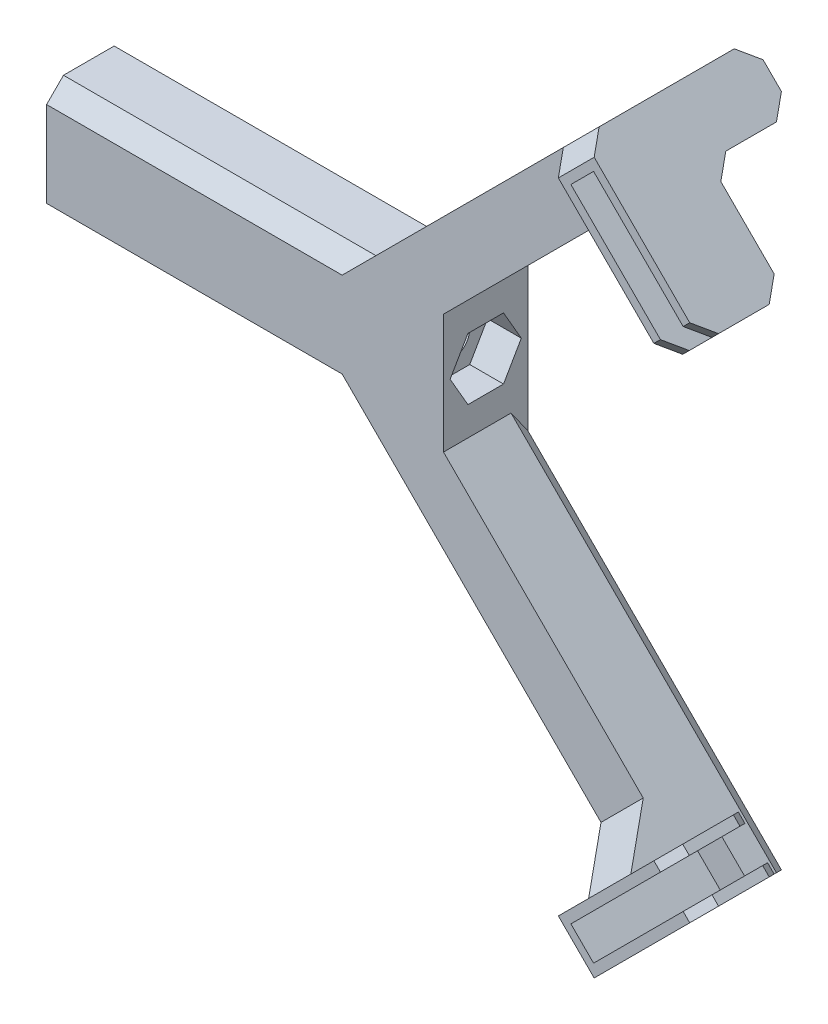
SolidWorks part; units mm, degrees
ref_plane "前视基准面" through (0, 0, 0) normal (0, 0, 1) x (1, 0, 0)
ref_plane "上视基准面" through (0, 0, 0) normal (0, 1, 0) x (1, 0, 0)
ref_plane "右视基准面" through (0, 0, 0) normal (1, 0, 0) x (0, 0, -1)
other "Configuration Table"
sketch "草图1" plane through (0, 0, 0) normal (0, 0, 1) x (1, 0, 0)
  line L0 (-10, 0) -> (33.5, 43.5)
  line L1 (33.5, 43.5) -> (38.5, 38.5)
  line L2 (38.5, 38.5) -> (0, 0)
  line L4 (0, 0) -> (43.2882, 0) construction
  line L5 (38.5, -38.5) -> (0, 0)
  line L6 (33.5, -43.5) -> (38.5, -38.5)
  line L7 (-10, 0) -> (33.5, -43.5)
  point P2 (-14.2991, 0)
  point P5 (18.3543, -31.7906)
  dimension "D1" = 90
  dimension "D2" = 10
  dimension "D3" = 38.5
extrude "凸台-拉伸1" add sketch "草图1" along normal mid plane 10
chamfer "倒角1" distance 10 angle 45 2 edges at (0, 0, 0) (-10, 0, 0)
sketch "草图2" plane through (-2.9289, 0, 0) normal (-1, 0, 0) x (0, 0, 1)
  circle A0 centre (0, 0) radius 2.1
  dimension "D1" = 4.2
extrude "切除-拉伸1" cut sketch "草图2" against normal through all and the other way through all
sketch "草图3" plane through (-2.9289, 0, 0) normal (-1, 0, 0) x (0, 0, 1)
  line L12 (5, -7.0711) -> (5, 7.0711)
  line L13 (5, 7.0711) -> (-5, 7.0711)
  line L14 (-5, 7.0711) -> (-5, -7.0711)
  line L15 (-5, -7.0711) -> (5, -7.0711)
  line L16 (5, -7.0711) -> (5, 7.0711)
  line L17 (5, 7.0711) -> (-5, 7.0711)
  line L18 (-5, 7.0711) -> (-5, -7.0711)
  line L19 (-5, -7.0711) -> (5, -7.0711)
  circle A0 centre (0, 0) radius 2.1 construction
  circle A1 centre (0, 0) radius 2.1
  dimension "D1" = 0
extrude "凸台-拉伸2" add sketch "草图3" along normal blind 37
sketch "草图4" plane through (38.5, 38.5, 0) normal (0.7071, 0.7071, 0) x (0, 0, -1)
  line L1 (-5, 7.0711) -> (-15, 7.0711)
  line L2 (-5, 7.0711) -> (-5, -12.9289)
  line L3 (-5, -12.9289) -> (-15, -12.9289)
  line L4 (-15, 7.0711) -> (-15, -12.9289)
  dimension "D1" = 20
  dimension "D2" = 10
extrude "凸台-拉伸3" add sketch "草图4" against normal blind 6
sketch "草图6" plane through (38.5, 38.5, 0) normal (0.7071, 0.7071, 0) x (0, 0, -1)
  line L0 (-5, -12.9289) -> (-5, 0) construction
  line L1 (-15, -12.9289) -> (-5, -12.9289)
  line L2 (-15, -12.9289) -> (-15, 19.0711)
  line L3 (-15, 19.0711) -> (-5, 19.0711)
  line L4 (-5, -12.9289) -> (-5, 19.0711)
  dimension "D1" = 32
extrude "凸台-拉伸5" add sketch "草图6" against normal blind 6
sketch "草图8" plane through (0, 0, 15) normal (0, 0, 1) x (1, 0, 0)
  line L0 (21.5499, 48.5205) -> (44.1773, 25.893)
  line L1 (20.7721, 47.7426) -> (25.0147, 51.9853) construction
  line L2 (43.3995, 25.1152) -> (47.6421, 29.3579) construction
  line L3 (44.1773, 25.893) -> (46.8643, 28.58)
  line L4 (46.8643, 28.58) -> (24.2369, 51.2075)
  line L5 (24.2369, 51.2075) -> (21.5499, 48.5205)
  line L6 (45.5208, 27.2365) -> (22.8934, 49.864) construction
  point P8 (24.4676, 51.4381)
  point P11 (0, 0)
  point P12 (28.4977, 55.4683)
  point P13 (0, 0)
  point P14 (50.9727, 32.6885)
  dimension "D1" = 3.8
extrude "切除-拉伸2" cut sketch "草图8" against normal blind 15
sketch "草图9" plane through (0, 0, 5) normal (0, 0, -1) x (-1, 0, 0)
  line L0 (-32.7222, 42.7222) -> (-24.2369, 51.2075) construction
  line L1 (-24.2369, 51.2075) -> (-25.0147, 51.9853) construction
  line L2 (-25.0147, 51.9853) -> (-33.5, 43.5) construction
  line L3 (-33.5, 43.5) -> (-32.7222, 42.7222) construction
  line L4 (-21.5499, 48.5205) -> (-30.0352, 40.0352) construction
  line L5 (-30.0352, 40.0352) -> (-29.2574, 39.2574) construction
  line L6 (-29.2574, 39.2574) -> (-20.7721, 47.7426) construction
  line L7 (-20.7721, 47.7426) -> (-21.5499, 48.5205) construction
  line L8 (-32.7222, 42.7222) -> (-24.2369, 51.2075)
  line L9 (-24.2369, 51.2075) -> (-25.0147, 51.9853)
  line L10 (-25.0147, 51.9853) -> (-33.5, 43.5)
  line L11 (-33.5, 43.5) -> (-32.7222, 42.7222)
  line L12 (-21.5499, 48.5205) -> (-30.0352, 40.0352)
  line L13 (-30.0352, 40.0352) -> (-29.2574, 39.2574)
  line L14 (-29.2574, 39.2574) -> (-20.7721, 47.7426)
  line L15 (-20.7721, 47.7426) -> (-21.5499, 48.5205)
extrude "切除-拉伸3" cut sketch "草图9" against normal through all
sketch "草图10" plane through (-5, 5, 0) normal (-0.7071, 0.7071, 0) x (0, 0, 1)
  line L0 (15, 49.5472) -> (15, 48.4472) construction
  line L1 (0, 53.3472) -> (15, 53.3472)
  line L2 (0, 53.3472) -> (0, 49.5472)
  line L3 (0, 49.5472) -> (15, 49.5472)
  line L4 (15, 53.3472) -> (15, 49.5472)
  line L5 (15, 49.5472) -> (0, 49.5472) construction
extrude "凸台-拉伸6" add sketch "草图10" against normal blind 3
chamfer "倒角2" distance 2 angle 45 8 edges at (15.2855, 25.2855, -5) (22.7855, 22.7855, -5) (38.1111, 38.1111, 5) (47.2532, 28.969, 5) (47.2532, 28.969, 15) (31.3787, 41.3787, 15) (43.7884, 25.5041, 5) (43.7884, 25.5041, 15)
mirror "镜向1" about plane through (0, 0, 0) normal (0, 1, 0) of "凸台-拉伸3", "凸台-拉伸5", "切除-拉伸2", "切除-拉伸3", "凸台-拉伸6"
chamfer "倒角3" distance 2 angle 45 9 edges at (34.6463, -34.6463, 5) (43.7884, -25.5041, 5) (43.7884, -25.5041, 15) (47.2532, -28.969, 5) (38.1111, -38.1111, 5) (22.7855, -22.7855, -5) (15.2855, -25.2855, -5) (31.3787, -41.3787, 15) (47.2532, -28.969, 15)
chamfer "倒角4" distance 5 angle 45 2 edges at (31.7574, -36.7574, 5) (31.7574, 36.7574, 5)
chamfer "倒角5" distance 2 angle 45 4 edges at (-20.0147, -7.0711, -5) (-20.0147, 7.0711, -5) (-21.4289, -7.0711, 5) (-21.4289, 7.0711, 5)
sketch "草图12" plane through (-39.9289, 0, 0) normal (-1, 0, 0) x (0, 0, 1)
  circle A0 centre (0, 0) radius 3.2
  dimension "D1" = 6.4
extrude "切除-拉伸4" cut sketch "草图12" against normal blind 38
sketch "草图13" plane through (7.0711, 0, 0) normal (1, 0, 0) x (0, 0, -1)
  line L1 (2.1073, -3.65) -> (4.2147, 0)
  line L2 (4.2147, 0) -> (2.1073, 3.65)
  line L3 (2.1073, 3.65) -> (-2.1073, 3.65)
  line L4 (-2.1073, 3.65) -> (-4.2147, 0)
  line L5 (-4.2147, 0) -> (-2.1073, -3.65)
  line L6 (-2.1073, -3.65) -> (2.1073, -3.65)
  circle A0 centre (0, 0) radius 3.65 construction
  dimension "D1" = 7.3
extrude "切除-拉伸5" cut sketch "草图13" against normal blind 4
